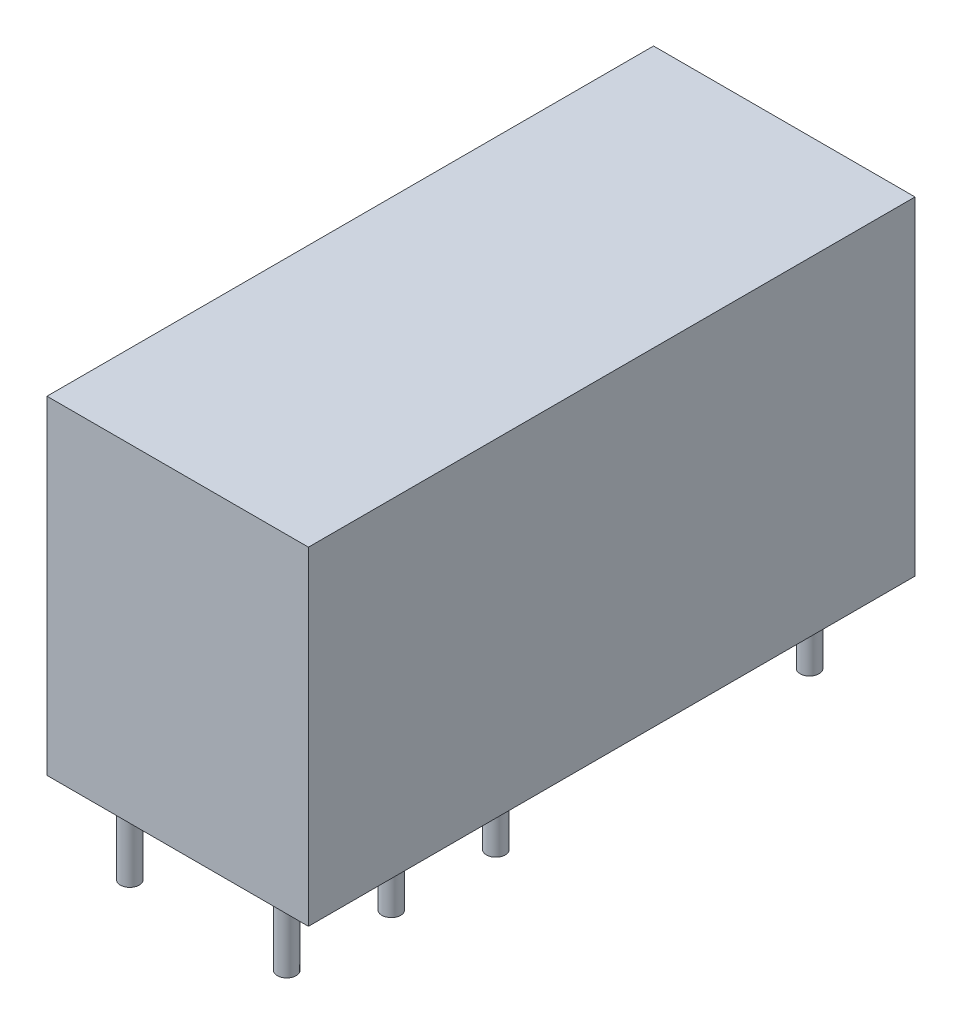
SolidWorks part; units mm, degrees
ref_plane "Front Plane" through (0, 0, 0) normal (0, 0, 1) x (1, 0, 0)
ref_plane "Top Plane" through (0, 0, 0) normal (0, 1, 0) x (1, 0, 0)
ref_plane "Right Plane" through (0, 0, 0) normal (1, 0, 0) x (0, 0, -1)
sketch "Sketch1" plane through (0, 0, 0) normal (0, 1, 0) x (1, 0, 0)
  line L1 (6.25, -14.5) -> (-6.25, -14.5)
  line L2 (6.25, -14.5) -> (6.25, 14.5)
  line L3 (6.25, 14.5) -> (-6.25, 14.5)
  line L4 (-6.25, -14.5) -> (-6.25, 14.5)
  line L5 (0, 14.5) -> (0, -14.5) construction
  line L6 (6.25, 0) -> (-6.25, 0) construction
  point P0 (0, 0)
  dimension "D1" = 29
  dimension "D2" = 12.5
extrude "Boss-Extrude1" add sketch "Sketch1" along normal blind 15.7
sketch "Sketch2" plane through (0, 0, 0) normal (0, 1, 0) x (1, 0, 0)
  line L0 (0, 0) -> (0, -15.3475) construction
  line L1 (6.25, 14.5) -> (-6.25, 14.5) construction
  circle A0 centre (-3.75, -13.04) radius 0.45
  circle A1 centre (-3.75, -8.04) radius 0.45
  circle A2 centre (-3.75, -3.04) radius 0.45
  circle A3 centre (-3.75, 11.96) radius 0.45
  circle A4 centre (3.75, 11.96) radius 0.45
  circle A5 centre (3.75, -3.04) radius 0.45
  circle A6 centre (3.75, -8.04) radius 0.45
  circle A7 centre (3.75, -13.04) radius 0.45
  point P11 (0, 0)
  dimension "D1" = 0.9
  dimension "D2" = 2.54
  dimension "D3" = 20
  dimension "D4" = 5
  dimension "D5" = 5
  dimension "D6" = 7.5
extrude "Boss-Extrude2" add sketch "Sketch2" against normal blind 3.8
